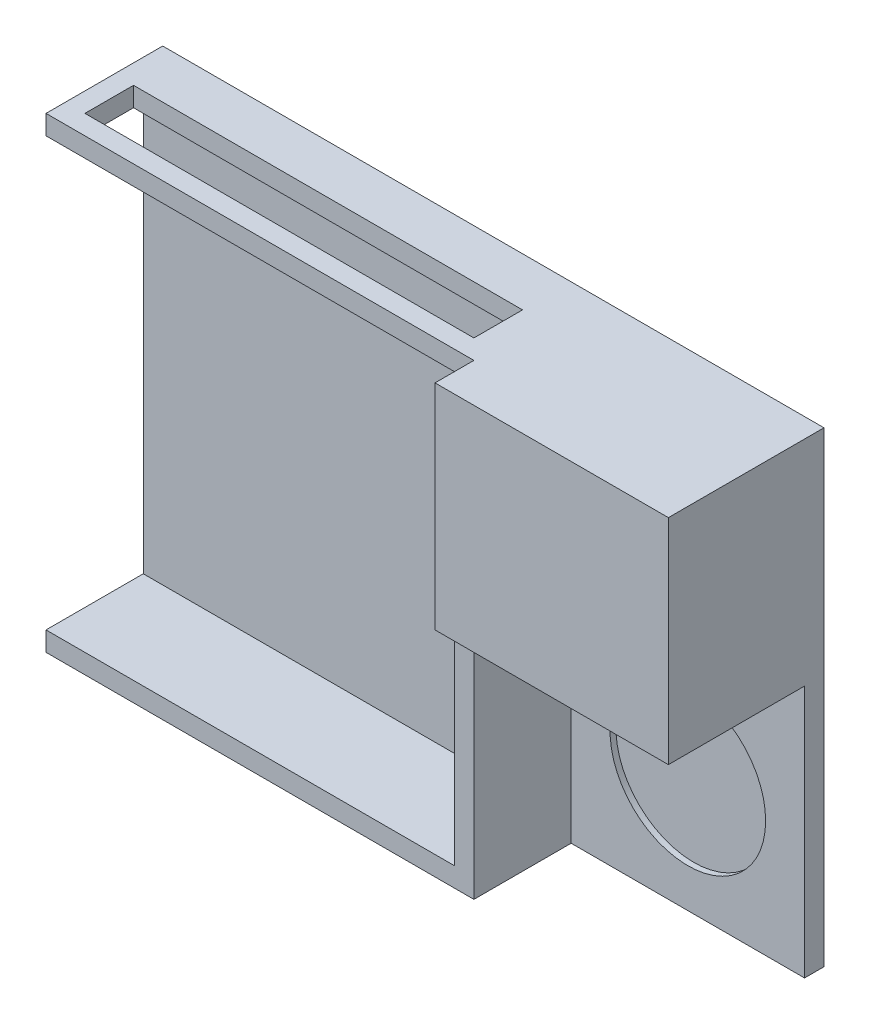
SolidWorks part; units mm, degrees
ref_plane "Plano frontal" through (0, 0, 0) normal (0, 0, 1) x (1, 0, 0)
ref_plane "Plano superior" through (0, 0, 0) normal (0, 1, 0) x (1, 0, 0)
ref_plane "Plano direito" through (0, 0, 0) normal (1, 0, 0) x (0, 0, -1)
sketch "Esboço1" plane through (0, 0, 0) normal (0, 0, 1) x (1, 0, 0)
  line L3 (-99.2177, 25.0239) -> (70.7823, 25.0239)
  line L4 (70.7823, 0) -> (70.7823, 25.0239)
  line L7 (-99.2177, 25.0239) -> (-269.2177, 25.0239)
  line L8 (-269.2177, 0) -> (-269.2177, 25.0239)
  line L11 (-99.2177, -214.9761) -> (-269.2177, -214.9761)
  line L12 (-269.2177, 0) -> (-269.2177, -214.9761)
  line L15 (-99.2177, -214.9761) -> (70.7823, -214.9761)
  line L16 (70.7823, 0) -> (70.7823, -214.9761)
  dimension "D1" = 340
  dimension "D2" = 240
extrude "Ressalto-extrusão1" add sketch "Esboço1" along normal blind 10 contours L7 L8 L12 L11 L15 L16 L4 L3
sketch "Esboço2" plane through (0, 0, 10) normal (0, 0, 1) x (1, 0, 0)
  line L8 (-49.2177, -214.9761) -> (-269.2177, -214.9761)
  line L9 (-49.2177, -214.9761) -> (-49.2177, -204.9761)
  line L10 (-49.2177, -204.9761) -> (-269.2177, -204.9761)
  line L11 (-269.2177, -214.9761) -> (-269.2177, -204.9761)
  line L12 (-269.2177, 25.0239) -> (-269.2177, -214.9761) construction
  line L13 (-269.2177, -214.9761) -> (70.7823, -214.9761) construction
  line L14 (-269.2177, 25.0239) -> (70.7823, 25.0239) construction
  line L15 (-49.2177, 25.0239) -> (-269.2177, 25.0239)
  line L16 (-49.2177, 25.0239) -> (-49.2177, 15.0239)
  line L17 (-49.2177, 15.0239) -> (-269.2177, 15.0239)
  line L18 (-269.2177, 25.0239) -> (-269.2177, 15.0239)
  line L20 (-49.2177, 15.0239) -> (-59.2177, 15.0239)
  line L21 (-49.2177, 15.0239) -> (-49.2177, -214.9761)
  line L22 (-49.2177, -214.9761) -> (-59.2177, -214.9761)
  line L23 (-59.2177, 15.0239) -> (-59.2177, -214.9761)
  dimension "D3" = 220
  dimension "D4" = 10
  dimension "D5" = 10
  dimension "D6" = 10
extrude "Ressalto-extrusão4" add sketch "Esboço2" along normal blind 50 contours L8 L11 L10 L9 | L16 L15 L18 L17 | L20 L23 L22 L21
sketch "Esboço7" plane through (0, 0, 10) normal (0, 0, 1) x (1, 0, 0)
  line L0 (70.7823, -214.9761) -> (70.7823, 25.0239) construction
  line L1 (10.7823, -214.9761) -> (10.7823, -154.9761)
  line L3 (-49.2177, -214.9761) -> (-49.2177, 25.0239) construction
  line L4 (-49.2177, -214.9761) -> (70.7823, -214.9761) construction
  line L5 (70.7823, -84.9761) -> (-49.2177, -84.9761)
  line L7 (70.7823, -84.9761) -> (70.7823, -74.9761)
  line L8 (70.7823, -74.9761) -> (-49.2177, -74.9761)
  line L9 (-49.2177, -84.9761) -> (-49.2177, -74.9761)
  circle A0 centre (10.7823, -154.9761) radius 40
  dimension "D2" = 80
  dimension "D1" = 60
  dimension "D3" = 60
  dimension "D4" = 70
  dimension "D5" = 10
extrude "Corte-extrusão1" cut sketch "Esboço7" against normal blind 3 contours A0
sketch "Esboço21" plane through (0, 25.0239, 0) normal (0, 1, 0) x (1, 0, 0)
  line L0 (-269.2177, -60) -> (-269.2177, 0) construction
  line L1 (-259.2177, -25) -> (-59.2177, -25)
  line L2 (-259.2177, -25) -> (-259.2177, -50)
  line L3 (-259.2177, -50) -> (-59.2177, -50)
  line L4 (-59.2177, -25) -> (-59.2177, -50)
  line L5 (-49.2177, -60) -> (-269.2177, -60) construction
  line L6 (70.7823, 0) -> (-269.2177, 0) construction
  dimension "D1" = 10
  dimension "D2" = 10
  dimension "D3" = 25
  dimension "D4" = 200
extrude "Corte-extrusão5" cut sketch "Esboço21" against normal blind 100 contours L1 L4 L3 L2
sketch "Esboço23" plane through (0, 15.0239, 0) normal (0, -1, 0) x (1, 0, 0)
  line L0 (-59.2177, 60) -> (-269.2177, 60) construction
  line L1 (-269.2177, 57.5) -> (-119.2177, 57.5)
  line L2 (-269.2177, 57.5) -> (-269.2177, 52.5)
  line L3 (-269.2177, 52.5) -> (-119.2177, 52.5)
  line L4 (-119.2177, 57.5) -> (-119.2177, 52.5)
  line L7 (-269.2177, 60) -> (-269.2177, 10) construction
  dimension "D1" = 5
  dimension "D2" = 2.5
  dimension "D3" = 150
  dimension "D4" = 0
extrude "Corte-extrusão6" cut sketch "Esboço23" against normal blind 1.25 and the other way blind 161.25 contours L1 L4 L3 L2
sketch "Esboço28" plane through (0, 0, 10) normal (0, 0, 1) x (1, 0, 0)
  line L0 (-49.2177, -214.9761) -> (-49.2177, 25.0239) construction
  line L2 (70.7823, -84.9761) -> (70.7823, 25.0239)
  line L3 (70.7823, -84.9761) -> (-49.2177, -84.9761)
  line L4 (-49.2177, -74.9761) -> (-49.2177, -84.9761)
  line L6 (-49.2177, 25.0239) -> (70.7823, 25.0239) construction
  line L9 (70.7823, 25.0239) -> (60.7823, 25.0239)
  line L13 (-49.2177, -74.9761) -> (-49.2177, 25.0239)
  line L14 (-49.2177, 25.0239) -> (-39.2177, 25.0239)
  line L16 (-39.2177, 25.0239) -> (60.7823, 25.0239)
  circle A0 centre (10.7823, -154.9761) radius 40 construction
  dimension "D2" = 70
extrude "Ressalto-extrusão5" add sketch "Esboço28" along normal blind 70 contours L2 L9 L16 L14 L13 L4 L3
